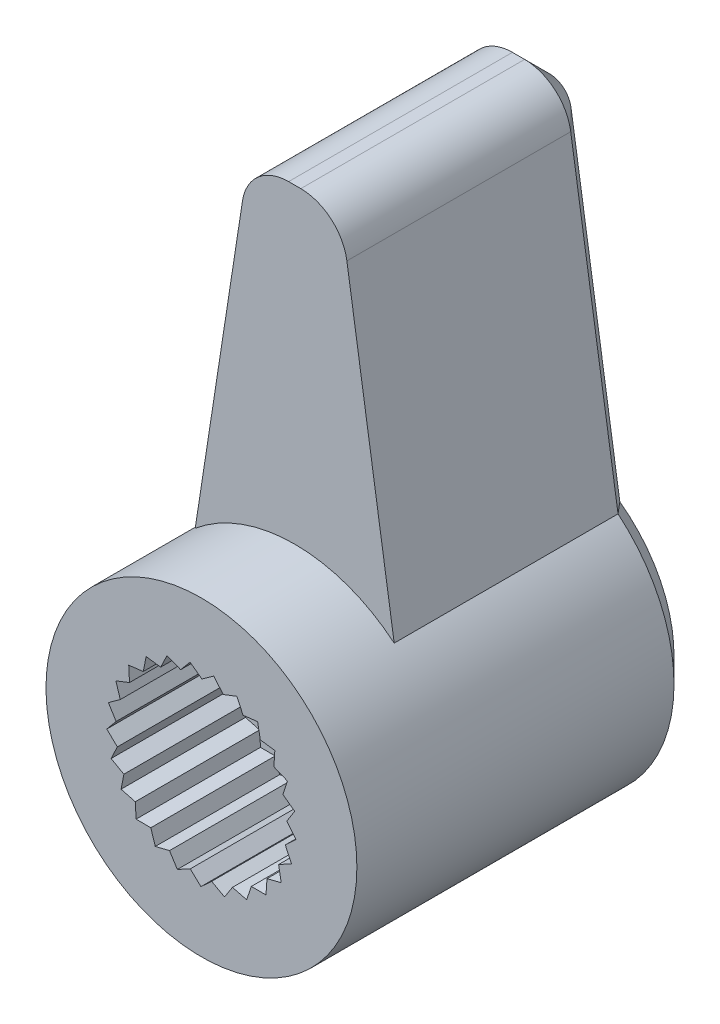
SolidWorks part; units mm, degrees
ref_plane "Front" through (0, 0, 0) normal (0, 0, 1) x (1, 0, 0)
ref_plane "Top" through (0, 0, 0) normal (0, 1, 0) x (1, 0, 0)
ref_plane "Right" through (0, 0, 0) normal (1, 0, 0) x (0, 0, -1)
sketch "Sketch1" plane through (0, 0, 0) normal (0, 0, 1) x (1, 0, 0)
  line L0 (0, 0) -> (0, 33.5454) construction
  line L1 (-0.196, 15) -> (0.196, 15) construction
  line L2 (-3.2, 3.8419) -> (-1.6786, 13.7282)
  line L3 (3.2, 3.8419) -> (1.6786, 13.7282)
  line L4 (-0.196, 15) -> (0.196, 15)
  arc A0 (-3.2, 3.8419) -> (3.2, 3.8419) centre (0, 0) ccw
  arc A4 (1.6786, 13.7282) -> (0.196, 15) centre (0.196, 13.5) ccw
  arc A5 (-0.196, 15) -> (-1.6786, 13.7282) centre (-0.196, 13.5) ccw
  circle A6 centre (0, 0) radius 1.5
  dimension "D1" = 10
  dimension "D11" = 1.5
  dimension "D9" = 1.5
  dimension "D12" = 3
  dimension "D2" = 15
  dimension "D10" = 3.2
extrude "Boss-Extrude3" add sketch "Sketch1" along normal blind 8
sketch "Sketch2" plane through (0, 0, 8) normal (0, 0, 1) x (1, 0, 0)
  circle A0 centre (0, 0) radius 5
  dimension "D1" = 10
extrude "Boss-Extrude4" add sketch "Sketch2" along normal blind 3
sketch "Sketch4" plane through (0, 0, 11) normal (0, 0, 1) x (1, 0, 0)
  line L0 (-5, 0) -> (5, 0) construction
  line L1 (0, 5) -> (0, -5) construction
  line L2 (0, 0) -> (-2.9927, 0.5883) construction
  line L3 (0, 0) -> (-2.8954, 0.9588) construction
  line L4 (0, 0) -> (-2.7524, 1.3141) construction
  line L5 (0, 0) -> (-2.566, 1.6487) construction
  line L6 (0, 0) -> (-2.3391, 1.9573) construction
  line L7 (0, 0) -> (-2.0753, 2.2351) construction
  line L8 (0, 0) -> (-1.7788, 2.4775) construction
  line L9 (0, 0) -> (-1.4543, 2.681) construction
  line L10 (0, 0) -> (-1.1068, 2.8421) construction
  line L11 (0, 0) -> (-0.7419, 2.9584) construction
  line L12 (0, 0) -> (-0.3653, 3.0281) construction
  line L13 (0, 0) -> (0.0171, 3.05) construction
  line L14 (0, 0) -> (0.3993, 3.0238) construction
  line L15 (0, 0) -> (0.7751, 2.9499) construction
  line L16 (0, 0) -> (1.1387, 2.8295) construction
  line L17 (0, 0) -> (1.4843, 2.6644) construction
  line L18 (0, 0) -> (1.8066, 2.4574) construction
  line L19 (0, 0) -> (2.1003, 2.2116) construction
  line L20 (0, 0) -> (2.361, 1.9309) construction
  line L21 (0, 0) -> (2.5843, 1.6198) construction
  line L22 (0, 0) -> (2.767, 1.2831) construction
  line L23 (0, 0) -> (2.906, 0.9262) construction
  line L24 (0, 0) -> (2.9991, 0.5547) construction
  line L25 (0, 0) -> (3.045, 0.1744) construction
  line L26 (0, 0) -> (3.0429, -0.2086) construction
  line L27 (0, 0) -> (2.9927, -0.5883) construction
  line L28 (0, 0) -> (2.8954, -0.9588) construction
  line L29 (0, 0) -> (2.7524, -1.3141) construction
  line L30 (0, 0) -> (2.566, -1.6487) construction
  line L31 (0, 0) -> (2.3391, -1.9573) construction
  line L32 (0, 0) -> (2.0753, -2.2351) construction
  line L33 (0, 0) -> (1.7788, -2.4775) construction
  line L34 (0, 0) -> (1.4543, -2.681) construction
  line L35 (0, 0) -> (1.1068, -2.8421) construction
  line L36 (0, 0) -> (0.7419, -2.9584) construction
  line L37 (0, 0) -> (0.3653, -3.0281) construction
  line L38 (0, 0) -> (-0.0171, -3.05) construction
  line L39 (0, 0) -> (-0.3993, -3.0238) construction
  line L40 (0, 0) -> (-0.7751, -2.9499) construction
  line L41 (0, 0) -> (-1.1387, -2.8295) construction
  line L42 (0, 0) -> (-1.4843, -2.6644) construction
  line L43 (0, 0) -> (-1.8066, -2.4574) construction
  line L44 (0, 0) -> (-2.1003, -2.2116) construction
  line L45 (0, 0) -> (-2.361, -1.9309) construction
  line L46 (0, 0) -> (-2.5843, -1.6198) construction
  line L47 (0, 0) -> (-2.767, -1.2831) construction
  line L48 (0, 0) -> (-2.906, -0.9262) construction
  line L49 (0, 0) -> (-2.9991, -0.5547) construction
  line L50 (0, 0) -> (-3.045, -0.1744) construction
  line L51 (0, 0) -> (-3.0429, 0.2086) construction
  line L52 (-2.9927, 0.5883) -> (-2.6106, 0.8645)
  line L53 (-2.6106, 0.8645) -> (-2.7524, 1.3141)
  line L54 (-2.7524, 1.3141) -> (-2.3136, 1.4866)
  line L55 (-2.3136, 1.4866) -> (-2.3391, 1.9573)
  line L56 (-2.3391, 1.9573) -> (-1.8712, 2.0152)
  line L57 (-1.8712, 2.0152) -> (-1.7788, 2.4775)
  line L58 (-1.7788, 2.4775) -> (-1.3113, 2.4173)
  line L59 (-1.3113, 2.4173) -> (-1.1068, 2.8421)
  line L60 (-1.1068, 2.8421) -> (-0.6689, 2.6674)
  line L61 (-0.6689, 2.6674) -> (-0.3653, 3.0281)
  line L62 (-0.3653, 3.0281) -> (0.0155, 2.75)
  line L63 (0.0155, 2.75) -> (0.3993, 3.0238)
  line L64 (0.3993, 3.0238) -> (0.6989, 2.6597)
  line L65 (0.6989, 2.6597) -> (1.1387, 2.8295)
  line L66 (1.1387, 2.8295) -> (1.3383, 2.4024)
  line L67 (1.3383, 2.4024) -> (1.8066, 2.4574)
  line L68 (1.8066, 2.4574) -> (1.8937, 1.9941)
  line L69 (1.8937, 1.9941) -> (2.361, 1.9309)
  line L70 (2.361, 1.9309) -> (2.3301, 1.4604)
  line L71 (2.3301, 1.4604) -> (2.767, 1.2831)
  line L72 (2.767, 1.2831) -> (2.6201, 0.8351)
  line L73 (2.6201, 0.8351) -> (2.9991, 0.5547)
  line L74 (2.9991, 0.5547) -> (2.7455, 0.1572)
  line L75 (2.7455, 0.1572) -> (3.0429, -0.2086)
  line L76 (3.0429, -0.2086) -> (2.6984, -0.5305)
  line L77 (2.6984, -0.5305) -> (2.8954, -0.9588)
  line L78 (2.8954, -0.9588) -> (2.4817, -1.1849)
  line L79 (2.4817, -1.1849) -> (2.566, -1.6487)
  line L80 (2.566, -1.6487) -> (2.109, -1.7648)
  line L81 (2.109, -1.7648) -> (2.0753, -2.2351)
  line L82 (2.0753, -2.2351) -> (1.6039, -2.2338)
  line L83 (1.6039, -2.2338) -> (1.4543, -2.681)
  line L84 (1.4543, -2.681) -> (0.998, -2.5625)
  line L85 (0.998, -2.5625) -> (0.7419, -2.9584)
  line L86 (0.7419, -2.9584) -> (0.3293, -2.7302)
  line L87 (0.3293, -2.7302) -> (-0.0171, -3.05)
  line L88 (-0.0171, -3.05) -> (-0.36, -2.7263)
  line L89 (-0.36, -2.7263) -> (-0.7751, -2.9499)
  line L90 (-0.7751, -2.9499) -> (-1.0267, -2.5512)
  line L91 (-1.0267, -2.5512) -> (-1.4843, -2.6644)
  line L92 (-1.4843, -2.6644) -> (-1.6289, -2.2157)
  line L93 (-1.6289, -2.2157) -> (-2.1003, -2.2116)
  line L94 (-2.1003, -2.2116) -> (-2.1287, -1.741)
  line L95 (-2.1287, -1.741) -> (-2.5843, -1.6198)
  line L96 (-2.5843, -1.6198) -> (-2.4948, -1.1569)
  line L97 (-2.4948, -1.1569) -> (-2.906, -0.9262)
  line L98 (-2.906, -0.9262) -> (-2.7041, -0.5001)
  line L99 (-2.7041, -0.5001) -> (-3.045, -0.1744)
  line L100 (-3.045, -0.1744) -> (-2.7436, 0.1881)
  line L101 (-2.7436, 0.1881) -> (-2.9927, 0.5883)
  circle A0 centre (0, 0) radius 5 construction
  arc A3 (3.2, 3.8419) -> (-3.2, 3.8419) centre (0, 0) ccw construction
  circle A4 centre (0, 0) radius 3.05 construction
  circle A5 centre (0, 0) radius 2.75 construction
  dimension "D1" = 6.1
  dimension "D2" = 0.3
  dimension "D3" = 50
extrude "Cut-Extrude1" cut sketch "Sketch4" against normal blind 4
sketch "Sketch5" plane through (0, 0, 0) normal (0, 0, -1) x (-1, 0, 0)
  circle A0 centre (0, 0) radius 2.4
  dimension "D1" = 4.8
extrude "Cut-Extrude2" cut sketch "Sketch5" against normal blind 4
chamfer "Chamfer1" distance 0.8 angle 45 7 edges at (2.4393, 8.785, 0) (1.1727, 14.6385, 0) (0, 15, 0) (-1.1727, 14.6385, 0) (-2.4393, 8.785, 0) (0, -5, 0) (-2.4, 0, 0)
